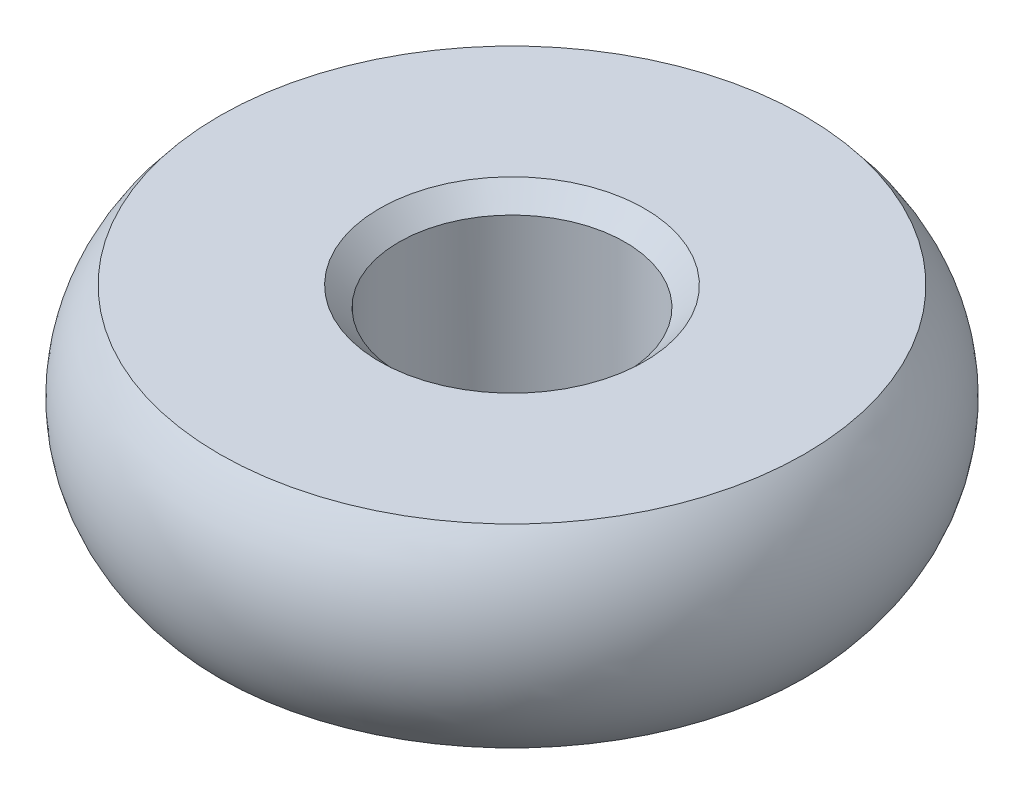
SolidWorks part; units mm, degrees
material "Custom Plastic"
ref_plane "Front Plane" through (0, 0, 0) normal (0, 0, 1) x (1, 0, 0)
ref_plane "Top Plane" through (0, 0, 0) normal (0, 1, 0) x (1, 0, 0)
ref_plane "Right Plane" through (0, 0, 0) normal (1, 0, 0) x (0, 0, -1)
sketch "Sketch1" plane through (0, 0, 0) normal (0, 0, 1) x (1, 0, 0)
  line L0 (0, -562.8227) -> (0, 27578.3136) construction
  line L1 (17.5, 15) -> (17.5, -15)
  line L2 (17.5, -15) -> (45.2705, -15)
  line L3 (17.5, 15) -> (45.2705, 15)
  arc A0 (45.2705, 15) -> (45.2705, -15) centre (28.5, 0) cw
  point P5 (17.5, 0)
  point P9 (51, 0)
  dimension "D3" = 22.5
  dimension "D1" = 30
  dimension "D2" = 17.5
  dimension "D4" = 102
revolve "Revolve1" add sketch "Sketch1" angle 360 about L0
chamfer "Chamfer1" distance 3 angle 45 2 edges at (17.5, 15, 0) (17.5, -15, 0)
